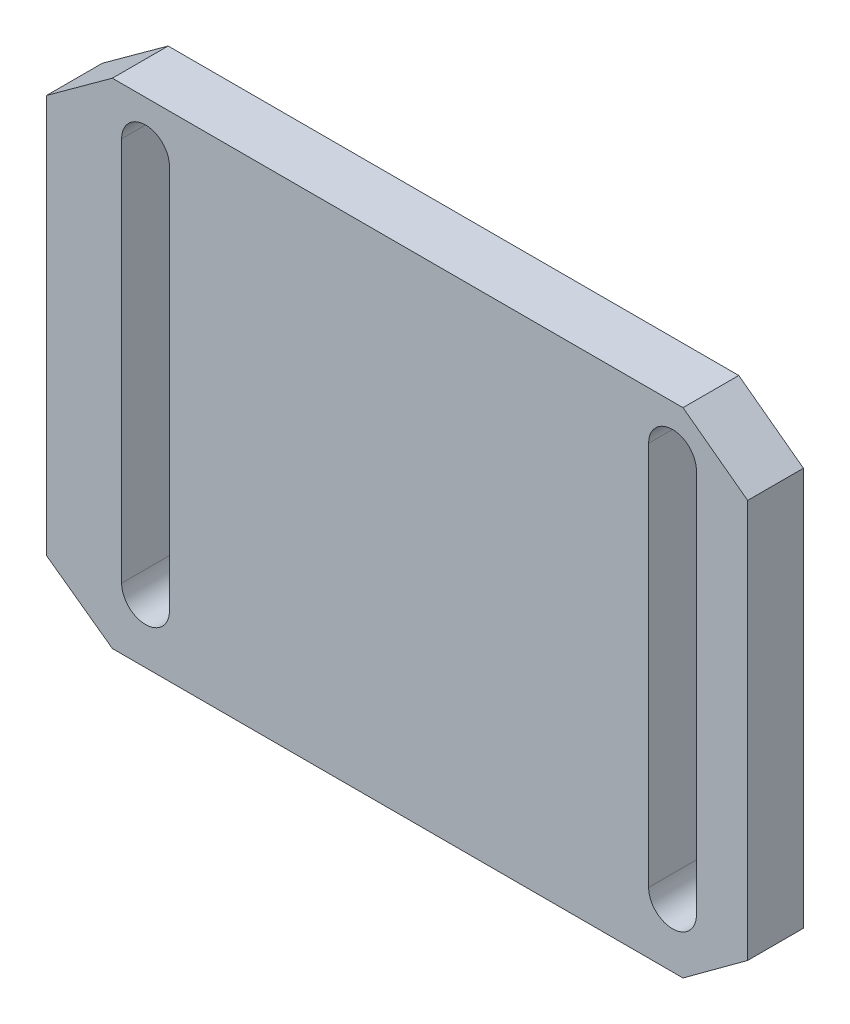
SolidWorks part; units mm, degrees
ref_plane "Front Plane" through (0, 0, 0) normal (0, 0, 1) x (1, 0, 0)
ref_plane "Top Plane" through (0, 0, 0) normal (0, 1, 0) x (1, 0, 0)
ref_plane "Right Plane" through (0, 0, 0) normal (1, 0, 0) x (0, 0, -1)
sketch "Sketch1" plane through (0, 0, 0) normal (0, 0, 1) x (1, 0, 0)
  line L1 (-79740.527, 61993.9134) -> (-8114.1458, 61993.9134)
  line L2 (-87997.4249, 55993.9134) -> (-87997.4249, 5957.0744)
  line L3 (-79740.527, -6.0866) -> (-8114.1458, -6.0866)
  line L4 (2.5751, 55969.0741) -> (2.5751, 5957.0744)
  line L6 (-79740.527, 61993.9134) -> (-87997.4249, 55993.9134)
  line L9 (-79740.527, -6.0866) -> (-87997.4249, 5957.0744)
  line L12 (2.5751, 55969.0741) -> (-8114.1458, 61993.9134)
  line L13 (-75575.7324, 55993.9134) -> (-75575.7324, 7685.3199) construction
  line L14 (-8114.1458, -6.0866) -> (2.5751, 5957.0744)
  line L15 (2.5751, -6.0866) -> (1344.6651, -6.0866)
  line L16 (-72575.7324, 55993.9134) -> (-72575.7324, 7685.3199)
  line L17 (-78575.7324, 55993.9134) -> (-78575.7324, 7685.3199)
  line L18 (-9427.3393, 55969.0741) -> (-9427.3393, 7685.3199) construction
  line L19 (-6427.3393, 55969.0741) -> (-6427.3393, 7685.3199)
  line L20 (-12427.3393, 55969.0741) -> (-12427.3393, 7685.3199)
  arc A0 (-72575.7324, 55993.9134) -> (-78575.7324, 55993.9134) centre (-75575.7324, 55993.9134) ccw
  arc A1 (-78575.7324, 7685.3199) -> (-72575.7324, 7685.3199) centre (-75575.7324, 7685.3199) ccw
  arc A2 (-6427.3393, 55969.0741) -> (-12427.3393, 55969.0741) centre (-9427.3393, 55969.0741) ccw
  arc A3 (-12427.3393, 7685.3199) -> (-6427.3393, 7685.3199) centre (-9427.3393, 7685.3199) ccw
  point P0 (-43997.4249, 30993.9134)
  point P8 (-75575.7324, 31839.6166)
  point P18 (-9427.3393, 31827.197)
  point P25 (0, 0)
  point P26 (0, 0)
extrude "Boss-Extrude1" add sketch "Sketch1" along normal blind 7000 contours L3 L14 L4 L12 L1 L6 L2 L9 | L17 A1 L16 A0 | L20 A3 L19 A2
sketch "Sketch3" plane through (0, 0, 7000) normal (0, 0, 1) x (1, 0, 0)
  line L0 (-75575.7324, 7685.3199) -> (-9427.3393, 55969.0741)
